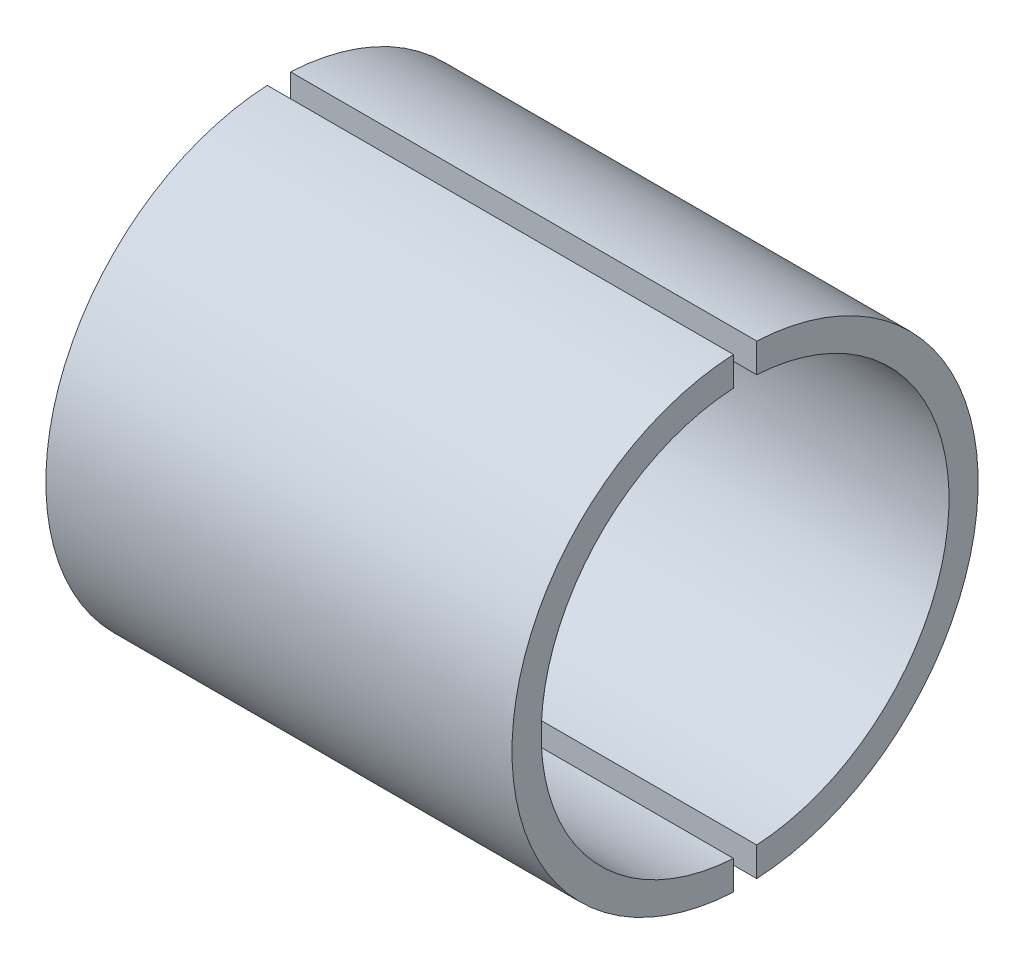
SolidWorks part; units mm, degrees
ref_plane "前视基准面" through (0, 0, 0) normal (0, 0, 1) x (1, 0, 0)
ref_plane "上视基准面" through (0, 0, 0) normal (0, 1, 0) x (1, 0, 0)
ref_plane "右视基准面" through (0, 0, 0) normal (1, 0, 0) x (0, 0, -1)
other "Configuration Table"
sketch "草图1" plane through (0, 0, 0) normal (1, 0, 0) x (0, 0, -1)
  circle A0 centre (0, 0) radius 20
  dimension "D1" = 40
extrude "凸台-拉伸1" add sketch "草图1" along normal blind 40
sketch "草图2" plane through (40, 0, 0) normal (1, 0, 0) x (0, 0, -1)
  circle A0 centre (0, 0) radius 17.5
  dimension "D1" = 35
extrude "切除-拉伸1" cut sketch "草图2" against normal blind 40
sketch "草图3" plane through (40, 0, 0) normal (1, 0, 0) x (0, 0, -1)
  line L0 (0, 20) -> (0, -20) construction
  line L2 (-1, 21.4787) -> (1, 21.4787)
  line L3 (-1, 21.4787) -> (-1, -22.1256)
  line L4 (-1, -22.1256) -> (1, -22.1256)
  line L5 (1, 21.4787) -> (1, -22.1256)
  circle A0 centre (0, 0) radius 20 construction
  dimension "D1" = 2
  dimension "D2" = 1
extrude "切除-拉伸2" cut sketch "草图3" against normal blind 40
